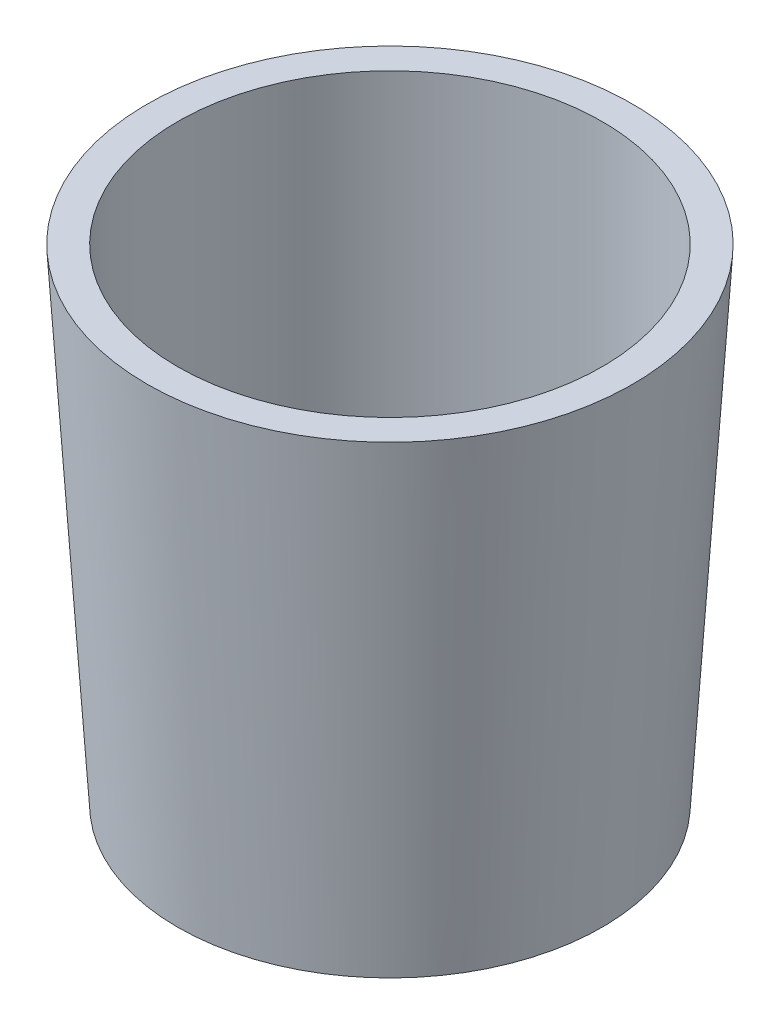
SolidWorks part; units mm, degrees
ref_plane "Alzado" through (0, 0, 0) normal (0, 0, 1) x (1, 0, 0)
ref_plane "Planta" through (0, 0, 0) normal (0, 1, 0) x (1, 0, 0)
ref_plane "Vista lateral" through (0, 0, 0) normal (1, 0, 0) x (0, 0, -1)
sketch "Croquis1" plane through (0, 0, 0) normal (0, 1, 0) x (1, 0, 0)
  circle A0 centre (0, 0) radius 35
  dimension "D1" = 70
ref_plane "Plano1" through (0, 80, 0) normal (0, 1, 0) x (1, 0, 0)
sketch "Croquis2" plane through (0, 80, 0) normal (0, 1, 0) x (1, 0, 0)
  circle A0 centre (0, 0) radius 40
  dimension "D1" = 80
loft "Recubrir1" add profiles "Croquis2", "Croquis1"
sketch "Croquis3" plane through (0, 80, 0) normal (0, 1, 0) x (1, 0, 0)
  circle A0 centre (0, 0) radius 35
extrude "Cortar-Extruir2" cut sketch "Croquis3" against normal blind 75
ref_plane "Plano2" through (0, 0, 37) normal (0, 0, 1) x (1, 0, 0)
sketch "Croquis5" plane through (0, 0, 37) normal (0, 0, 1) x (1, 0, 0)
  line L0 (14.1509, 72.7047) -> (34.5343, 72.7047) construction
  line L1 (14.1509, 75) -> (34.5343, 75)
  line L2 (14.1509, 70.4094) -> (34.5343, 70.4094)
  line L3 (44.0001, 80) -> (-44.0001, 80) construction
  line L4 (35, 0) -> (40, 80) construction
  arc A0 (14.1509, 75) -> (14.1509, 70.4094) centre (14.1509, 72.7047) ccw
  arc A1 (34.5343, 70.4094) -> (34.5343, 75) centre (34.5343, 72.7047) ccw
  point P2 (24.3426, 72.7047)
  dimension "D2" = 2.2953
  dimension "D3" = 5
  dimension "D1" = 5
